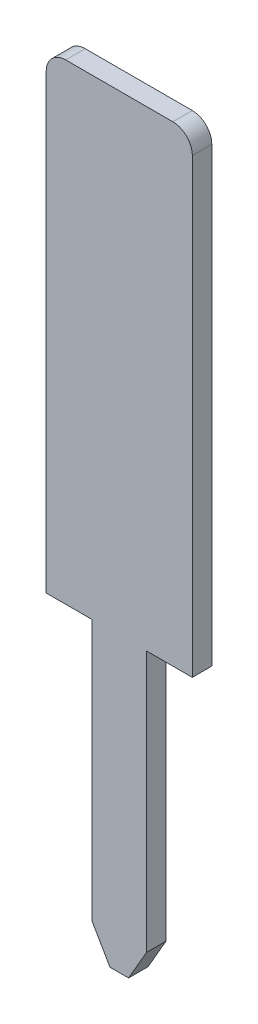
SolidWorks part; units mm, degrees
material "Pure Gold"
ref_plane "Front Plane" through (0, 0, 0) normal (0, 0, 1) x (1, 0, 0)
ref_plane "Top Plane" through (0, 0, 0) normal (0, 1, 0) x (1, 0, 0)
ref_plane "Right Plane" through (0, 0, 0) normal (1, 0, 0) x (0, 0, -1)
sketch "Sketch1" plane through (0, 0, 0) normal (0, 0, 1) x (1, 0, 0)
  line L0 (-49.1053, -44.1202) -> (-49.1053, -54.2802) construction
  line L1 (-49.1053, -48.1334) -> (-47.2003, -48.1334)
  line L2 (-49.1053, -48.1334) -> (-49.1053, -54.2802)
  line L3 (-47.2003, -54.2802) -> (-47.2003, -48.1334)
  line L4 (-47.2003, -54.2802) -> (-47.2003, 17.6018) construction
  line L5 (-48.1528, -48.1334) -> (-48.1528, -59.7278) construction
  line L6 (-48.5084, -54.2802) -> (-48.5084, -57.6842)
  line L7 (-48.274, -58.0902) -> (-48.0317, -58.0902)
  line L8 (-47.7972, -54.2802) -> (-47.7972, -57.6842)
  line L9 (-48.5084, -54.2802) -> (-49.1053, -54.2802)
  line L10 (-48.5084, -57.6842) -> (-48.274, -58.0902)
  line L11 (-47.7972, -57.6842) -> (-48.0317, -58.0902)
  line L12 (-49.1053, -54.2802) -> (-47.2003, -54.2802) construction
  line L15 (-47.7972, -54.2802) -> (-47.2003, -54.2802)
  dimension "D2" = 30
  dimension "D3" = 6.1468
  dimension "D4" = 0.7112
extrude "Boss-Extrude1" add sketch "Sketch1" along normal blind 0.254
fillet "Fillet2" radius 0.254 2 edges at (-49.1053, -48.1334, 0.127) (-47.2003, -48.1334, 0.127)
